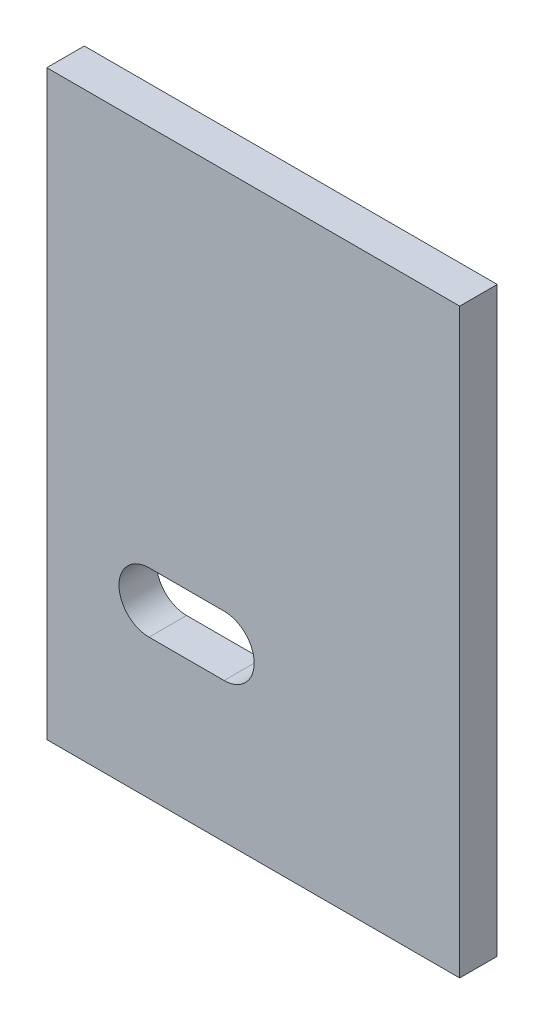
SolidWorks part; units mm, degrees
ref_plane "前视基准面" through (0, 0, 0) normal (0, 0, 1) x (1, 0, 0)
ref_plane "上视基准面" through (0, 0, 0) normal (0, 1, 0) x (1, 0, 0)
ref_plane "右视基准面" through (0, 0, 0) normal (1, 0, 0) x (0, 0, -1)
sketch "草图1" plane through (0, 0, 0) normal (0, 0, 1) x (1, 0, 0)
  line L1 (-55, -77.5) -> (55, -77.5)
  line L2 (-55, -77.5) -> (-55, 77.5)
  line L3 (-55, 77.5) -> (55, 77.5)
  line L4 (55, -77.5) -> (55, 77.5)
  line L5 (-55, -77.5) -> (55, 77.5) construction
  line L6 (-55, 77.5) -> (55, -77.5) construction
  point P0 (0, 0)
  dimension "D1" = 155
  dimension "D2" = 110
extrude "凸台-拉伸1" add sketch "草图1" along normal blind 10
sketch "草图2" plane through (0, 0, 10) normal (0, 0, 1) x (1, 0, 0)
  line L0 (-55, 77.5) -> (-55, -77.5) construction
  line L1 (-55, -77.5) -> (55, -77.5) construction
  line L2 (-27.75, -32.25) -> (-7.75, -32.25) construction
  line L3 (-27.75, -24.25) -> (-7.75, -24.25)
  line L4 (-27.75, -40.25) -> (-7.75, -40.25)
  circle A0 centre (-27.75, -32.25) radius 8 construction
  arc A1 (-27.75, -24.25) -> (-27.75, -40.25) centre (-27.75, -32.25) ccw
  arc A2 (-7.75, -40.25) -> (-7.75, -24.25) centre (-7.75, -32.25) ccw
  point P7 (-17.75, -32.25)
  dimension "D1" = 27.25
  dimension "D3" = 16
  dimension "D2" = 45.25
  dimension "D4" = 20
extrude "切除-拉伸1" cut sketch "草图2" against normal through all both and the other way through all
